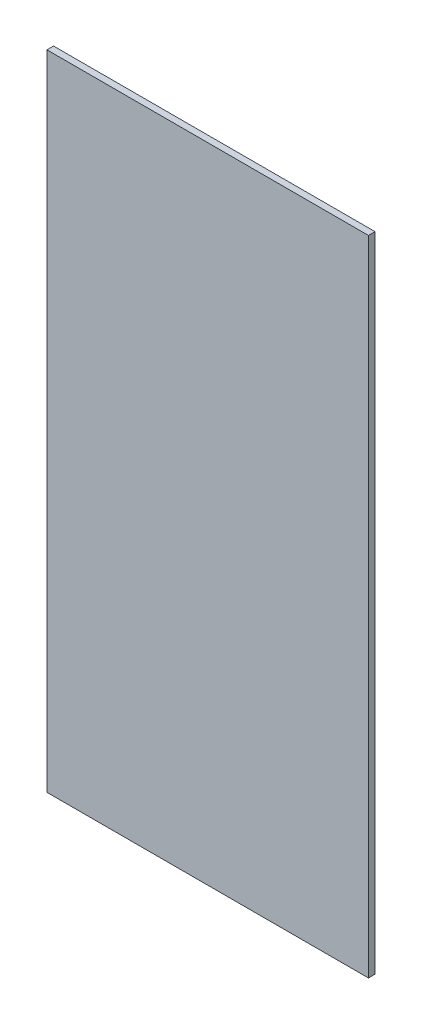
SolidWorks part; units mm, degrees
ref_plane "Front Plane" through (0, 0, 0) normal (0, 0, 1) x (1, 0, 0)
ref_plane "Top Plane" through (0, 0, 0) normal (0, 1, 0) x (1, 0, 0)
ref_plane "Right Plane" through (0, 0, 0) normal (1, 0, 0) x (0, 0, -1)
sketch "Sketch1" plane through (0, 0, 0) normal (0, 0, 1) x (1, 0, 0)
  line L1 (-304.8, 609.6) -> (304.8, 609.6)
  line L2 (-304.8, 609.6) -> (-304.8, -609.6)
  line L3 (-304.8, -609.6) -> (304.8, -609.6)
  line L4 (304.8, 609.6) -> (304.8, -609.6)
  line L5 (-304.8, 609.6) -> (304.8, -609.6) construction
  line L6 (-304.8, -609.6) -> (304.8, 609.6) construction
  point P0 (0, 0)
  dimension "D1" = 609.6
  dimension "D2" = 1219.2
extrude "Boss-Extrude1" add sketch "Sketch1" along normal blind 12.5
